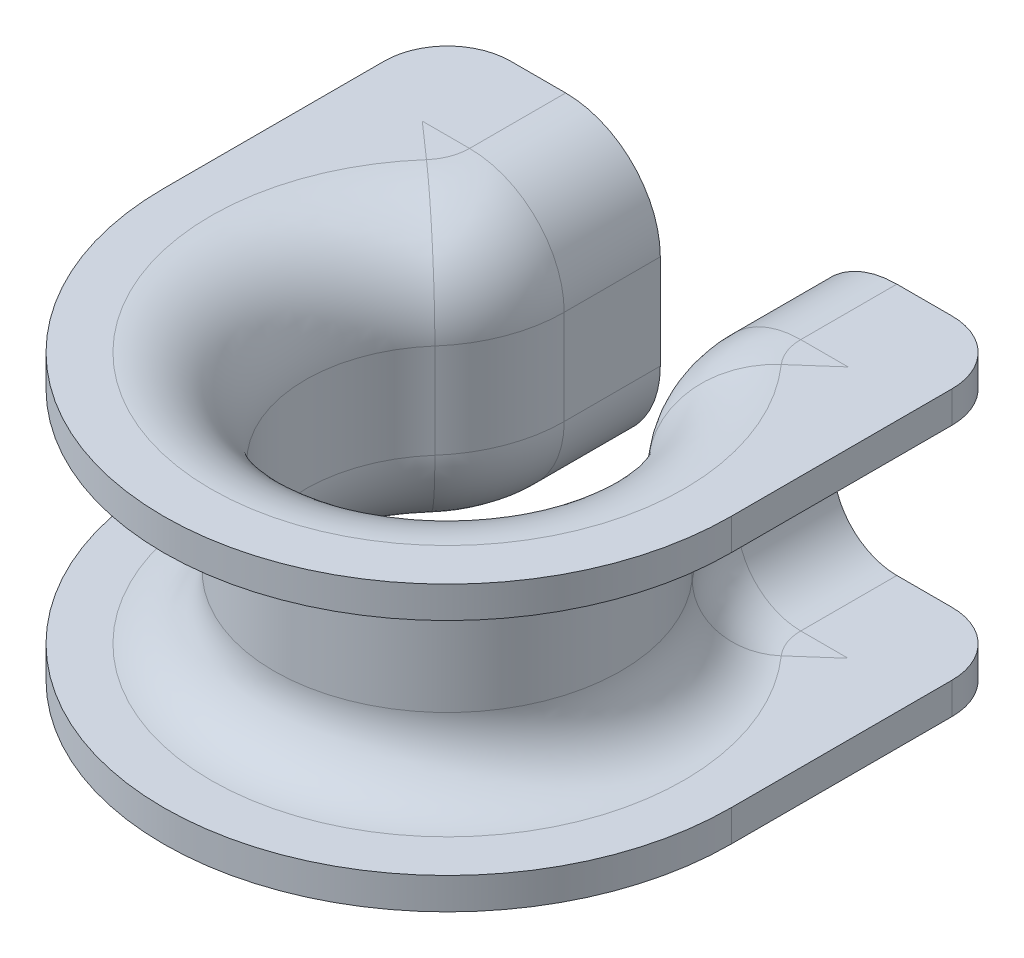
SolidWorks part; units mm, degrees
ref_plane "Front Plane" through (0, 0, 0) normal (0, 0, 1) x (1, 0, 0)
ref_plane "Top Plane" through (0, 0, 0) normal (0, 1, 0) x (1, 0, 0)
ref_plane "Right Plane" through (0, 0, 0) normal (1, 0, 0) x (0, 0, -1)
sketch "Sketch2" plane through (0, 0, 0) normal (0, 1, 0) x (1, 0, 0)
  line L0 (0, 16.8409) -> (0, -11.7913) construction
  line L1 (-4.5, 18) -> (-4.5, 11.9059)
  line L2 (4.5, 18) -> (4.5, 11.9059)
  line L3 (-4.5, 18) -> (4.5, 18) construction
  arc A0 (-6.75, 5.9529) -> (6.75, 5.9529) centre (0, 0) ccw
  arc A1 (4.5, 11.9059) -> (6.75, 5.9529) centre (13.5, 11.9059) ccw
  arc A2 (-4.5, 11.9059) -> (-6.75, 5.9529) centre (-13.5, 11.9059) cw
  point P9 (0, 18)
  point P10 (5.5331, 16.5186)
  dimension "D1" = 18
  dimension "D4" = 9
  dimension "D2" = 9
  dimension "D3" = 18
sketch "Sketch3" plane through (0, 0, 0) normal (1, 0, 0) x (0, 0, -1)
  line L0 (-9, 3) -> (-9, -3)
  line L3 (-1.5235, 0) -> (-30.742, 0) construction
  line L4 (5.9529, 0) -> (-9, 0) construction
  line L11 (-15, 3) -> (-15, -3) construction
  line L15 (-11, 3) -> (-11, -3)
  line L17 (-15, 9) -> (-18, 9)
  line L18 (-18, 9) -> (-18, 7)
  line L19 (-18, 7) -> (-15, 7)
  line L20 (-15, -9) -> (-18, -9)
  line L21 (-18, -9) -> (-18, -7)
  line L22 (-18, -7) -> (-15, -7)
  line L23 (-15, 9) -> (-15, -9) construction
  arc A10 (-9, 3) -> (-15, 9) centre (-15, 3) ccw
  arc A11 (-15, -9) -> (-9, -3) centre (-15, -3) ccw
  arc A13 (-15, -7) -> (-11, -3) centre (-15, -3) ccw
  arc A14 (-11, 3) -> (-15, 7) centre (-15, 3) ccw
  point P3 (-15, 0)
  point P11 (-15, 0)
  point P12 (-15, 9)
  point P13 (-15, -9)
  dimension "D1" = 12
  dimension "D4" = 9
  dimension "D2" = 18
  dimension "D3" = 12
  dimension "D5" = 2
  dimension "D6" = 2
  dimension "D7" = 3
  dimension "D8" = 3
sweep "Sweep2" add profiles "Sketch3" path "Sketch2"
sketch "Sketch4" plane through (0, 9, 0) normal (0, 1, 0) x (1, 0, 0)
  line L0 (-13.5, 18) -> (-14, 18)
  line L1 (-18, 14) -> (-18, 0)
  line L2 (13.5, 18) -> (14, 18)
  line L3 (18, 14) -> (18, 0)
  line L4 (-13.5, 18) -> (-13.5, 11.9059)
  line L5 (13.5, 18) -> (13.5, 11.9059)
  arc A0 (-13.5, 11.9059) -> (13.5, 11.9059) centre (0, 0) ccw construction
  arc A1 (14, 18) -> (18, 14) centre (14, 14) cw
  arc A2 (-14, 18) -> (-18, 14) centre (-14, 14) ccw
  arc A3 (-13.5, 11.9059) -> (-18, 0) centre (0, 0) ccw
  arc A4 (13.5, 11.9059) -> (18, 0) centre (0, 0) cw
  line M6 (-13.5, 18) -> (-13.5, 11.9059)
  dimension "D1" = 4
extrude "Boss-Extrude1" add sketch "Sketch4" against normal blind 2 contours A3 L0 A2 L1 M6 | L5 A4 L3 A1 L2
mirror "Mirror2" about plane through (0, 0, 0) normal (0, 1, 0) of "Boss-Extrude1"
